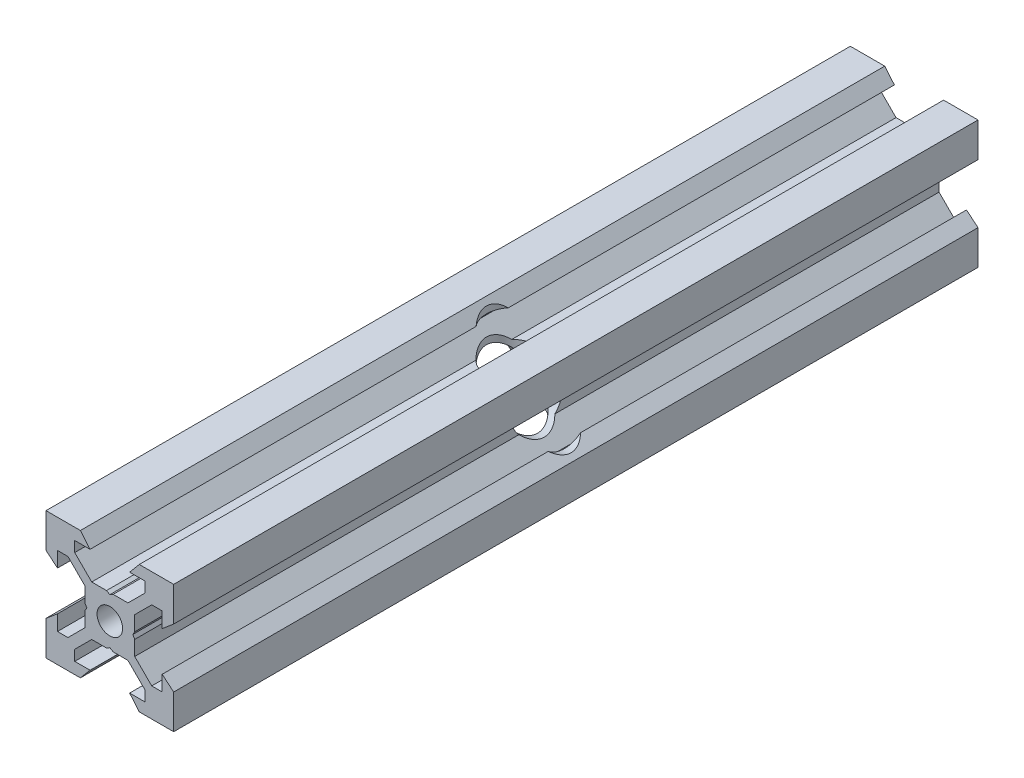
SolidWorks part; units mm, degrees
material "3.3535 (EN-AW 5754)"
ref_plane "Front Plane" through (0, 0, 0) normal (0, 0, 1) x (1, 0, 0)
ref_plane "Top Plane" through (0, 0, 0) normal (0, 1, 0) x (1, 0, 0)
ref_plane "Right Plane" through (0, 0, 0) normal (1, 0, 0) x (0, 0, -1)
sketch "Sketch1" plane through (0, 0, 0) normal (0, 0, 1) x (1, 0, 0)
  line L0 (10, 10) -> (4.6104, 10) construction
  line L1 (10, 10) -> (10, 4.6104) construction
  line L2 (10, -10) -> (10, -4.6104) construction
  line L3 (10, -10) -> (4.6104, -10) construction
  line L4 (10, 10) -> (10, 4.6104)
  line L5 (6.5607, 5.5) -> (8.2, 5.5)
  line L6 (5.5, 8.2) -> (5.5, 6.5607)
  line L7 (10, 10) -> (4.6104, 10)
  line L8 (10, 10) -> (10, 4.6104)
  line L9 (6.5607, 5.5) -> (3.9, 2.8393)
  line L10 (5.5, 6.5607) -> (2.8393, 3.9)
  line L11 (10, 4.6104) -> (8.2, 3.1)
  line L12 (4.6104, 10) -> (3.1, 8.2)
  line L13 (8.2, 3.1) -> (8.2, 5.5)
  line L14 (3.1, 8.2) -> (5.5, 8.2)
  line L15 (-6.5607, 5.5) -> (-8.2, 5.5)
  line L16 (6.5607, -5.5) -> (8.2, -5.5)
  line L17 (3.1, -8.2) -> (5.5, -8.2)
  line L18 (8.2, -3.1) -> (8.2, -5.5)
  line L19 (4.6104, -10) -> (3.1, -8.2)
  line L20 (10, -4.6104) -> (8.2, -3.1)
  line L21 (0.5196, -3.9) -> (0, -3.6)
  line L22 (0.5196, 3.9) -> (0, 3.6)
  line L23 (3.6, 0) -> (3.9, -0.5196)
  line L24 (3.9, 0.5196) -> (3.6, 0)
  line L25 (3.9, 0.5196) -> (3.9, 2.8393)
  line L26 (2.8393, 3.9) -> (0.5196, 3.9)
  line L27 (3.9, -2.8393) -> (3.9, -0.5196)
  line L28 (2.8393, -3.9) -> (0.5196, -3.9)
  line L29 (5.5, -6.5607) -> (2.8393, -3.9)
  line L30 (6.5607, -5.5) -> (3.9, -2.8393)
  line L31 (10, -10) -> (10, -4.6104)
  line L32 (10, -10) -> (4.6104, -10)
  line L33 (5.5, -8.2) -> (5.5, -6.5607)
  line L34 (-6.5607, -5.5) -> (-8.2, -5.5)
  line L35 (10, -10) -> (10, -4.6104)
  line L36 (0, 0) -> (0, 8.2) construction
  line L37 (-10, -10) -> (-4.6104, -10) construction
  line L38 (-10, -10) -> (-10, -4.6104) construction
  line L39 (-10, 10) -> (-10, 4.6104) construction
  line L40 (-10, 10) -> (-4.6104, 10) construction
  line L41 (-10, -10) -> (-10, -4.6104)
  line L43 (-5.5, -8.2) -> (-5.5, -6.5607)
  line L44 (-10, -10) -> (-4.6104, -10)
  line L45 (-10, -10) -> (-10, -4.6104)
  line L46 (-6.5607, -5.5) -> (-3.9, -2.8393)
  line L47 (-5.5, -6.5607) -> (-2.8393, -3.9)
  line L48 (-2.8393, -3.9) -> (-0.5196, -3.9)
  line L49 (-3.9, -2.8393) -> (-3.9, -0.5196)
  line L50 (-2.8393, 3.9) -> (-0.5196, 3.9)
  line L51 (-3.9, 0.5196) -> (-3.9, 2.8393)
  line L52 (-3.9, 0.5196) -> (-3.6, 0)
  line L53 (-3.6, 0) -> (-3.9, -0.5196)
  line L54 (-0.5196, 3.9) -> (0, 3.6)
  line L55 (-0.5196, -3.9) -> (0, -3.6)
  line L56 (-10, -4.6104) -> (-8.2, -3.1)
  line L57 (-4.6104, -10) -> (-3.1, -8.2)
  line L58 (-8.2, -3.1) -> (-8.2, -5.5)
  line L59 (-3.1, -8.2) -> (-5.5, -8.2)
  line L60 (-10, -10) -> (10, -10) construction
  line L61 (-10, -10) -> (-10, 10) construction
  line L62 (-3.1, 8.2) -> (-5.5, 8.2)
  line L63 (-8.2, 3.1) -> (-8.2, 5.5)
  line L64 (-4.6104, 10) -> (-3.1, 8.2)
  line L65 (-10, 4.6104) -> (-8.2, 3.1)
  line L66 (-5.5, 6.5607) -> (-2.8393, 3.9)
  line L67 (-6.5607, 5.5) -> (-3.9, 2.8393)
  line L68 (-10, 10) -> (-10, 4.6104)
  line L69 (-10, 10) -> (-4.6104, 10)
  line L70 (-5.5, 8.2) -> (-5.5, 6.5607)
  line L71 (-10, 10) -> (10, 10) construction
  line L72 (-10, 10) -> (-10, 4.6104)
  line L73 (10, -10) -> (10, 10) construction
  line L74 (-10, -10) -> (10, 10) construction
  line L75 (-10, 10) -> (10, -10) construction
  circle A0 centre (0, 0) radius 2
  dimension "D7" = 4
  dimension "D1" = 20
  dimension "D2" = 5.3896
  dimension "D3" = 4.5
  dimension "D4" = 50
  dimension "D5" = 1.8
  dimension "D6" = 1.5104
  dimension "D8" = 5.5
  dimension "D9" = 120
  dimension "D10" = 0.3
  dimension "D11" = 2.3197
  dimension "D12" = 7.8
  dimension "D13" = 7.8
  dimension "D14" = 1.5
  dimension "D15" = 2.6607
extrude "Boss-Extrude1" add sketch "Sketch1" along normal blind 126 contours L70 L62 L64 L69 L68 L65 L63 L15 L67 L51 L52 L53 L49 L46 L34 L58 L56 L41 L44 L57 L59 L43 L47 L48 L55 L21 L28 L29 L33 L17 L19 L32 L31 L20 L18 L16 L30 L27 L23 L24 L25 L9 L5 L13 L11 L4 L7 L12 L14 L6 L10
sketch "Sketch4" plane through (0, 0, 0) normal (1, 0, 0) x (0, 0, -1)
  line L0 (-126, 0) -> (0, 0) construction
  circle A0 centre (-63, 0) radius 4
  dimension "D1" = 8
extrude "Cut-Extrude1" cut sketch "Sketch4" against normal through all both and the other way through all
sketch "Sketch5" plane through (0, 0, 0) normal (0, 1, 0) x (1, 0, 0)
  line L0 (0, 0) -> (0, -126) construction
  circle A0 centre (0, -63) radius 4
  dimension "D1" = 8
extrude "Cut-Extrude2" cut sketch "Sketch5" against normal through all both and the other way through all
